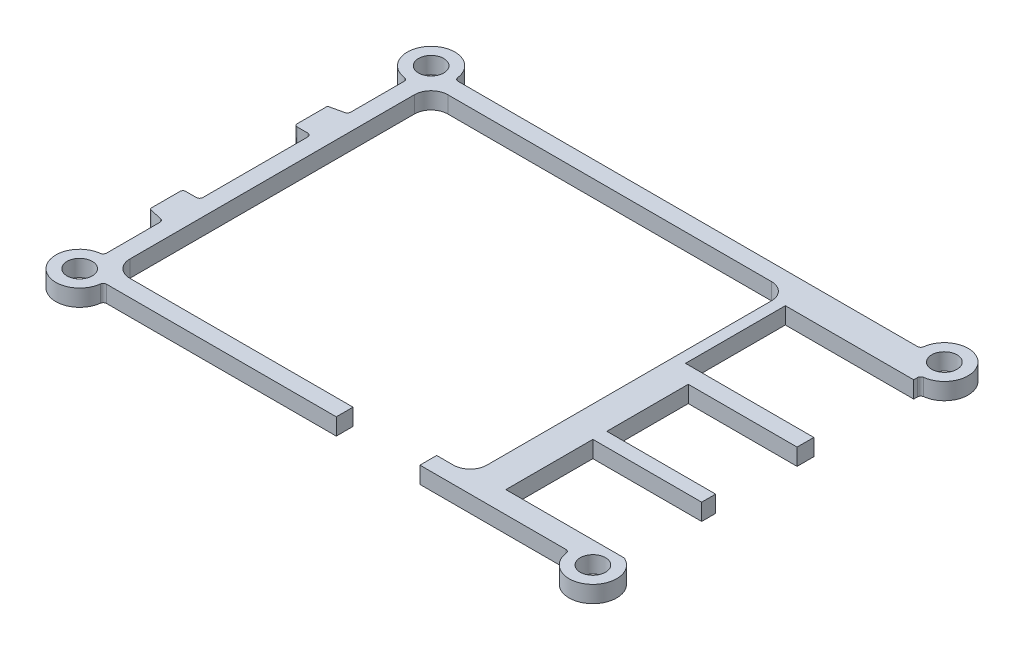
SolidWorks part; units mm, degrees
material "Balsa"
ref_plane "Front Plane" through (0, 0, 0) normal (0, 0, 1) x (1, 0, 0)
ref_plane "Top Plane" through (0, 0, 0) normal (0, 1, 0) x (1, 0, 0)
ref_plane "Right Plane" through (0, 0, 0) normal (1, 0, 0) x (0, 0, -1)
sketch "Sketch1" plane through (0, 0, 0) normal (0, 1, 0) x (1, 0, 0)
  line L0 (46, 0) -> (46, -63) construction
  line L5 (4.265, 0) -> (87.735, 0)
  line L6 (3.2, -3.25) -> (88.8, -3.25) construction
  line L7 (3.2, -3.25) -> (3.2, -59.75) construction
  line L8 (3.2, -59.75) -> (88.8, -59.75) construction
  line L9 (88.8, -3.25) -> (88.8, -59.75) construction
  line L10 (3.2, -3.25) -> (88.8, -59.75) construction
  line L11 (3.2, -59.75) -> (88.8, -3.25) construction
  line L12 (0, -4.265) -> (0, -58.735)
  line L14 (92, -4.265) -> (92, -58.735)
  line L15 (4.265, -63) -> (87.735, -63)
  circle A0 centre (0, 0) radius 2.265
  circle A1 centre (92, 0) radius 2.265
  circle A2 centre (92, -63) radius 2.265
  circle A3 centre (0, -63) radius 2.265
  arc A4 (4.265, 0) -> (0, -4.265) centre (0, 0) ccw
  arc A5 (92, -4.265) -> (87.735, 0) centre (92, 0) ccw
  arc A6 (87.735, -63) -> (92, -58.735) centre (92, -63) ccw
  arc A7 (0, -58.735) -> (4.265, -63) centre (0, -63) ccw
  point P7 (46, -31.5)
  dimension "D5" = 4.53
  dimension "D6" = 2
  dimension "D1" = 92
  dimension "D2" = 63
  dimension "D3" = 85.6
  dimension "D4" = 56.5
extrude "Boss-Extrude1" add sketch "Sketch1" along normal blind 3
sketch "Sketch2" plane through (0, 3, 0) normal (0, 1, 0) x (1, 0, 0)
  line L0 (0, -31.5) -> (92, -31.5) construction
  line L1 (0, -4.265) -> (0, -58.735) construction
  line L2 (92, -58.735) -> (92, -4.265) construction
  line L4 (0, -21.5) -> (6.5, -21.5)
  line L5 (0, -21.5) -> (0, -41.5)
  line L6 (0, -41.5) -> (6.5, -41.5)
  line L7 (6.5, -21.5) -> (6.5, -41.5)
  point P11 (0, -31.5)
  dimension "D1" = 20
  dimension "D2" = 6.5
extrude "Cut-Extrude1" cut sketch "Sketch2" against normal blind 3
sketch "Sketch3" plane through (0, 3, 0) normal (0, 1, 0) x (1, 0, 0)
  line L0 (-2.7, -15.5) -> (0, -14.9)
  line L1 (0, -21.5) -> (-2.5, -21.5)
  line L2 (0, -21.5) -> (0, -14.9)
  line L4 (-3, -21) -> (-3, -15.8)
  line L5 (6.5, -31.5) -> (-19.974, -31.5) construction
  line L6 (6.5, -41.5) -> (6.5, -21.5) construction
  line L7 (-3, -42) -> (-3, -47.2)
  line L8 (0, -41.5) -> (-2.5, -41.5)
  line L9 (0, -41.5) -> (0, -48.1)
  line L10 (-2.7, -47.5) -> (0, -48.1)
  arc A0 (-3, -21) -> (-2.5, -21.5) centre (-2.5, -21) ccw
  arc A1 (-3, -15.8) -> (-2.7, -15.5) centre (-2.7, -15.8) cw
  arc A2 (-3, -47.2) -> (-2.7, -47.5) centre (-2.7, -47.2) ccw
  arc A3 (-3, -42) -> (-2.5, -41.5) centre (-2.5, -42) cw
  point P7 (-3, -21.5)
  point P10 (-3, -15.5)
  dimension "D3" = 0.5
  dimension "D4" = 0.3
  dimension "D1" = 3
  dimension "D2" = 6
  dimension "D5" = 6.6
extrude "Boss-Extrude2" add sketch "Sketch3" against normal blind 3
sketch "Sketch4" plane through (0, 3, 0) normal (0, 1, 0) x (1, 0, 0)
  line L0 (0, -4.265) -> (0, -14.9) construction
  line L1 (6, -3) -> (64, -3)
  line L2 (3, -6) -> (3, -57)
  line L3 (6, -60) -> (64, -60)
  line L4 (67, -6) -> (67, -57)
  line L6 (4.265, -63) -> (87.735, -63) construction
  line L7 (87.735, 0) -> (4.265, 0) construction
  arc A0 (6, -60) -> (3, -57) centre (6, -57) cw
  arc A1 (67, -57) -> (64, -60) centre (64, -57) cw
  arc A2 (67, -6) -> (64, -3) centre (64, -6) ccw
  arc A3 (3, -6) -> (6, -3) centre (6, -6) cw
  dimension "D5" = 3
  dimension "D1" = 3
  dimension "D2" = 3
  dimension "D3" = 3
  dimension "D4" = 67
extrude "Cut-Extrude2" cut sketch "Sketch4" against normal blind 3
sketch "Sketch5" plane through (0, 3, 0) normal (0, 1, 0) x (1, 0, 0)
  line L0 (-2.5, -41.5) -> (3, -41.5) construction
  line L1 (3, -21.5) -> (0, -21.5)
  line L2 (3, -21.5) -> (3, -41.5)
  line L3 (3, -41.5) -> (0, -41.5)
  line L4 (0, -21.5) -> (0, -41.5)
extrude "Boss-Extrude3" add sketch "Sketch5" against normal blind 3
sketch "Sketch6" plane through (0, 3, 0) normal (0, 1, 0) x (1, 0, 0)
  line L0 (67, -57) -> (67, -6) construction
  line L1 (69, -5.5) -> (96.0101, -5.5)
  line L2 (69, -5.5) -> (69, -23.4)
  line L3 (69, -23.4) -> (96.0101, -23.4)
  line L4 (96.0101, -5.5) -> (96.0101, -23.4)
  line L5 (87.735, 0) -> (4.265, 0) construction
  dimension "D1" = 2
  dimension "D2" = 17.9
  dimension "D3" = 5.5
extrude "Cut-Extrude3" cut sketch "Sketch6" against normal blind 3
sketch "Sketch7" plane through (0, 3, 0) normal (0, 1, 0) x (1, 0, 0)
  line L0 (92, -58.735) -> (92, -23.4) construction
  line L1 (72.5, -26.4) -> (92, -26.4)
  line L2 (72.5, -26.4) -> (72.5, -41)
  line L3 (72.5, -41) -> (92, -41)
  line L4 (92, -26.4) -> (92, -41)
  line L5 (69, -23.4) -> (92, -23.4) construction
  line L6 (67, -57) -> (67, -6) construction
  line L7 (4.265, -63) -> (87.735, -63) construction
  dimension "D1" = 3
  dimension "D2" = 5.5
  dimension "D3" = 22
extrude "Cut-Extrude4" cut sketch "Sketch7" against normal blind 3
sketch "Sketch8" plane through (0, 3, 0) normal (0, 1, 0) x (1, 0, 0)
  line L0 (92, -58.735) -> (92, -41) construction
  line L1 (72.5, -43.5) -> (92, -43.5)
  line L2 (72.5, -43.5) -> (72.5, -59.1)
  line L3 (72.5, -59.1) -> (92, -59.1)
  line L4 (92, -43.5) -> (92, -59.1)
  line L5 (72.5, -41) -> (92, -41) construction
  line L6 (67, -57) -> (67, -6) construction
  line L7 (4.265, -63) -> (87.735, -63) construction
  dimension "D1" = 2.5
  dimension "D2" = 5.5
  dimension "D3" = 3.9
extrude "Cut-Extrude5" cut sketch "Sketch8" against normal blind 3
sketch "Sketch9" plane through (0, 3, 0) normal (0, 1, 0) x (1, 0, 0)
  line L1 (92, -59.1) -> (94.0196, -59.1)
  line L2 (92, -59.1) -> (92, -58.5257)
  line L3 (92, -58.5257) -> (94.0196, -58.5257)
  line L4 (94.0196, -59.1) -> (94.0196, -58.5257)
extrude "Cut-Extrude6" cut sketch "Sketch9" against normal blind 3
sketch "Sketch10" plane through (0, 3, 0) normal (0, 1, 0) x (1, 0, 0)
  line L0 (6, -60) -> (64, -60) construction
  line L1 (46, -60) -> (61, -60)
  line L2 (46, -60) -> (46, -63)
  line L3 (46, -63) -> (61, -63)
  line L4 (61, -60) -> (61, -63)
  line L5 (4.265, -63) -> (87.735, -63) construction
  line L6 (3, -6) -> (3, -57) construction
  line L7 (67, -57) -> (67, -6) construction
  dimension "D1" = 43
  dimension "D2" = 6
extrude "Cut-Extrude7" cut sketch "Sketch10" against normal blind 3
fillet "Fillet1" radius 0.6 12 edges at (87.735, 1.5, 0) (92, 1.5, 4.265) (93.7263, 1.5, 59.1) (87.735, 1.5, 63) (4.265, 1.5, 63) (0, 1.5, 58.735) (0, 1.5, 48.1) (0, 1.5, 41.5) (4.265, 1.5, 0) (0, 1.5, 14.9) (0, 1.5, 4.265) (0, 1.5, 21.5)
